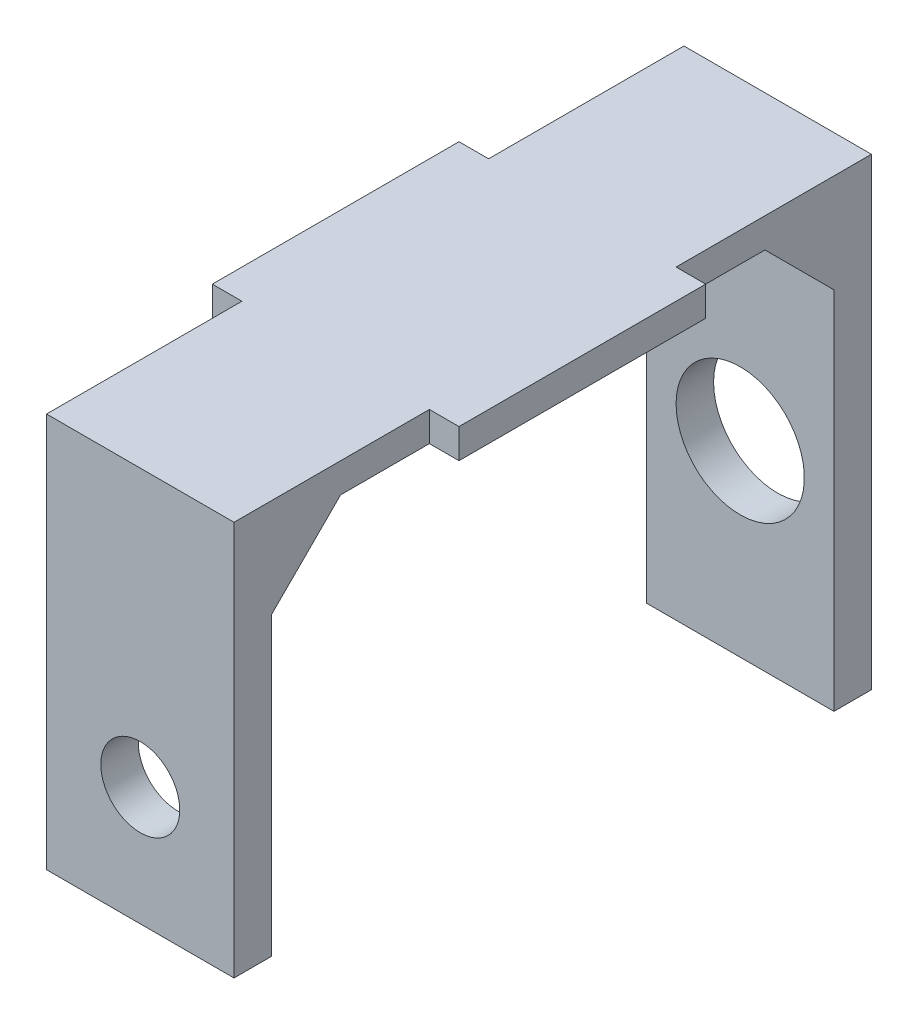
SolidWorks part; units mm, degrees
ref_plane "Ön Düzlem" through (0, 0, 0) normal (0, 0, 1) x (1, 0, 0)
ref_plane "Üst Düzlem" through (0, 0, 0) normal (0, 1, 0) x (1, 0, 0)
ref_plane "Sağ Düzlem" through (0, 0, 0) normal (1, 0, 0) x (0, 0, -1)
sketch "Çizim1" plane through (0, 0, 0) normal (0, 1, 0) x (1, 0, 0)
  line L1 (-9.5, 60.8) -> (-9.5, 57)
  line L2 (9.5, 57) -> (9.5, 60.8)
  line L3 (9.5, 60.8) -> (-9.5, 60.8)
  line L4 (-9.5, 57) -> (9.5, 57)
  line L5 (-9.5, 0) -> (-9.5, -3.8)
  line L6 (-9.5, -3.8) -> (9.5, -3.8)
  line L7 (9.5, -3.8) -> (9.5, 0)
  line L8 (9.5, 0) -> (-9.5, 0)
  dimension "D2" = 3.8
  dimension "D3" = 19
extrude "Yükseklik-Ekstrüzyon1" add sketch "Çizim1" along normal blind 50
sketch "Çizim2" plane through (0, 50, 0) normal (0, 1, 0) x (1, 0, 0)
  line L0 (-9.5, 60.8) -> (-9.5, 41)
  line L1 (-9.5, -3.8) -> (9.5, -3.8)
  line L2 (9.5, -3.8) -> (9.5, 16)
  line L3 (9.5, 60.8) -> (-9.5, 60.8)
  line L5 (-9.5, 16) -> (-9.5, -3.8)
  line L6 (-12.5, 41) -> (-9.5, 41)
  line L7 (-12.5, 41) -> (-12.5, 16)
  line L8 (-12.5, 16) -> (-9.5, 16)
  line L9 (12.5, 41) -> (12.5, 16)
  line L12 (9.5, 41) -> (12.5, 41)
  line L14 (9.5, 41) -> (9.5, 60.8)
  line L15 (9.5, 16) -> (12.5, 16)
  point P9 (0, 0)
extrude "Yükseklik-Ekstrüzyon2" add sketch "Çizim2" along normal blind 3
sketch "Çizim3" plane through (0, 0, -60.8) normal (0, 0, -1) x (-1, 0, 0)
  circle A0 centre (0, 25) radius 6.5
extrude "Kes-Ekstrüzyon1" cut sketch "Çizim3" against normal blind 5
sketch "Çizim4" plane through (0, 0, 0) normal (0, 0, -1) x (-1, 0, 0)
  circle A1 centre (0, 25) radius 4
extrude "Kes-Ekstrüzyon2" cut sketch "Çizim4" against normal blind 5
sketch "Çizim5" plane through (0, 0, -60.8) normal (0, 0, -1) x (-1, 0, 0)
  line L1 (-9.5, 6) -> (9.5, 6)
  line L2 (-9.5, 53) -> (-9.5, 0) construction
  line L3 (9.5, 53) -> (9.5, 0) construction
  line L4 (9.5, 6) -> (9.5, 0)
  line L5 (9.5, 0) -> (-9.5, 0)
  line L6 (-9.5, 0) -> (-9.5, 6)
extrude "Kes-Ekstrüzyon3" cut sketch "Çizim5" against normal blind 73
sketch "Çizim6" plane through (0, 0, 3.8) normal (0, 0, 1) x (1, 0, 0)
  line L3 (-9.5, 13) -> (9.5, 13)
  line L4 (-9.5, 13) -> (-9.5, 6)
  line L5 (-9.5, 6) -> (9.5, 6)
  line L6 (9.5, 13) -> (9.5, 6)
  line L7 (-9.5, 13) -> (9.5, 6) construction
  line L8 (-9.5, 6) -> (9.5, 13) construction
  point P5 (0, 9.5)
extrude "Kes-Ekstrüzyon4" cut sketch "Çizim6" against normal blind 9
sketch "Çizim7" plane through (9.5, 0, 0) normal (1, 0, 0) x (0, 0, -1)
  line L0 (57, 50) -> (57, 43)
  line L1 (57, 50) -> (57, 6) construction
  line L2 (57, 43) -> (50, 50)
  line L3 (41, 50) -> (57, 50) construction
  line L4 (50, 50) -> (57, 50)
  line L5 (0, 50) -> (0, 43)
  line L6 (0, 50) -> (0, 13) construction
  line L7 (0, 43) -> (7, 50)
  line L8 (0, 50) -> (16, 50) construction
  line L9 (7, 50) -> (0, 50)
extrude "Yükseklik-Ekstrüzyon3" add sketch "Çizim7" against normal blind 19
